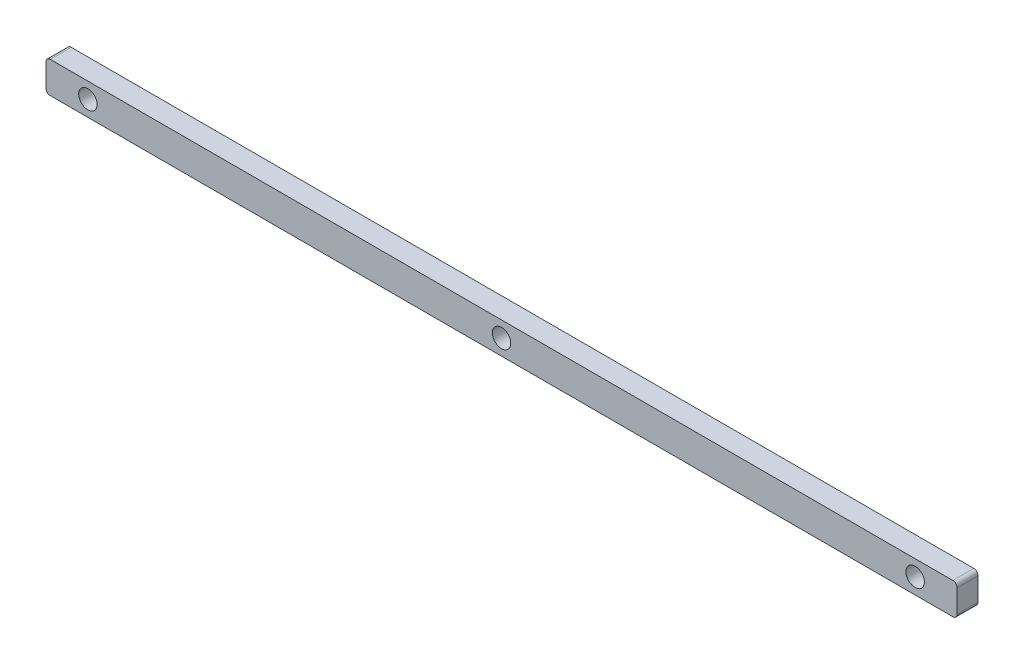
SolidWorks part; units mm, degrees
material "Balsa"
ref_plane "Front Plane" through (0, 0, 0) normal (0, 0, 1) x (1, 0, 0)
ref_plane "Top Plane" through (0, 0, 0) normal (0, 1, 0) x (1, 0, 0)
ref_plane "Right Plane" through (0, 0, 0) normal (1, 0, 0) x (0, 0, -1)
sketch "Sketch1" plane through (0, 0, 0) normal (0, 0, 1) x (1, 0, 0)
  line L1 (-276.225, -9.525) -> (276.225, -9.525)
  line L2 (-276.225, -9.525) -> (-276.225, 9.525)
  line L3 (-276.225, 9.525) -> (276.225, 9.525)
  line L4 (276.225, -9.525) -> (276.225, 9.525)
  circle A0 centre (0, 0) radius 5.588
  circle A1 centre (-250.825, 0) radius 5.588
  circle A2 centre (250.825, 0) radius 5.588
  point P0 (0, 0)
  point P12 (0, 0)
  point P13 (0, 0)
  dimension "D3" = 11.176
  dimension "D4" = 11.176
  dimension "D5" = 11.176
  dimension "D1" = 552.45
  dimension "D2" = 19.05
  dimension "D6" = 25.4
  dimension "D7" = 25.4
  dimension "D8" = 9.525
  dimension "D9" = 250.825
extrude "Boss-Extrude1" add sketch "Sketch1" along normal mid plane 12.7
fillet "Fillet1" radius 2.54 4 edges at (-276.225, 9.525, 0) (-276.225, -9.525, 0) (276.225, -9.525, 0) (276.225, 9.525, 0)
